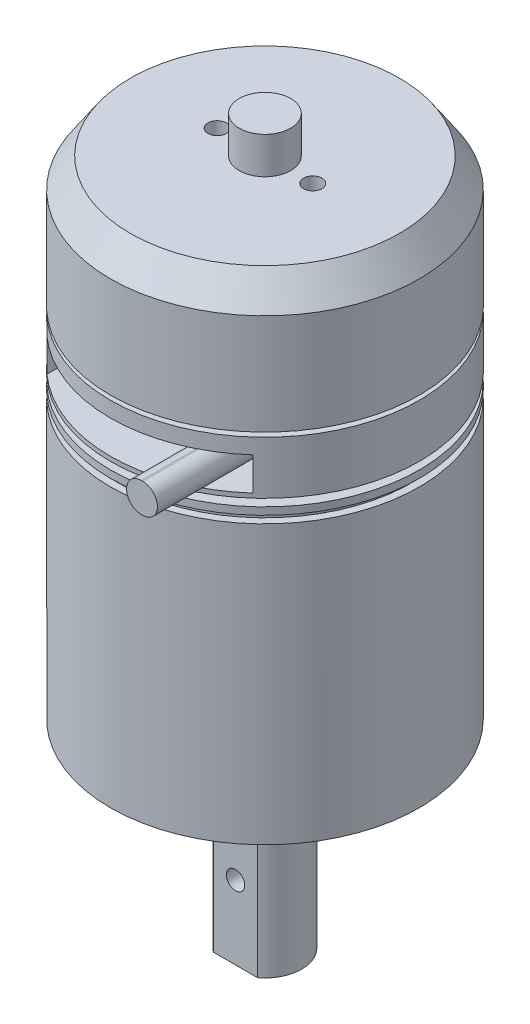
SolidWorks part; units mm, degrees
ref_plane "前视基准面" through (0, 0, 0) normal (0, 0, 1) x (1, 0, 0)
ref_plane "上视基准面" through (0, 0, 0) normal (0, 1, 0) x (1, 0, 0)
ref_plane "右视基准面" through (0, 0, 0) normal (1, 0, 0) x (0, 0, -1)
sketch "草图1" plane through (0, 0, 0) normal (0, 0, 1) x (1, 0, 0)
  line L0 (0, 0) -> (4.1, 0)
  line L1 (4.1, 0) -> (4.1, 6.7)
  line L2 (4.1, 6.7) -> (13.4, 6.7)
  line L3 (13.4, 6.7) -> (13.4, 8.7)
  line L4 (13.4, 8.7) -> (21, 8.7)
  line L5 (21, 8.7) -> (21, 10.2)
  line L6 (21, 10.2) -> (20, 10.2)
  line L7 (20, 10.2) -> (20, 11.2)
  line L8 (20, 11.2) -> (21, 11.2)
  line L9 (21, 11.2) -> (21, 12.2)
  line L10 (21, 12.2) -> (10, 12.2)
  line L11 (10, 12.2) -> (10, 13.2)
  line L12 (10, 13.2) -> (21, 13.2)
  line L13 (21, 13.2) -> (21, 20.4)
  line L14 (21, 20.4) -> (5, 20.4)
  line L15 (5, 20.4) -> (5, 21)
  line L16 (5, 21) -> (21, 21)
  line L17 (21, 21) -> (21, 34.7)
  line L18 (21, 34.7) -> (18.3, 38.7)
  line L19 (18.3, 38.7) -> (3.5, 38.7)
  line L20 (3.5, 38.7) -> (3.5, 43.7)
  line L21 (3.5, 43.7) -> (0, 43.7)
  line L22 (0, 43.7) -> (0, 0) construction
  line L23 (0, 0) -> (0, 43.7)
  dimension "D1" = 8.2
  dimension "D2" = 26.8
  dimension "D3" = 42
  dimension "D4" = 10
  dimension "D5" = 1.5
  dimension "D6" = 1
  dimension "D7" = 1
  dimension "D8" = 20
  dimension "D9" = 1
  dimension "D10" = 7.2
  dimension "D11" = 0.6
  dimension "D12" = 13.7
  dimension "D13" = 5
  dimension "D14" = 2
  dimension "D15" = 6.7
  dimension "D16" = 1
  dimension "D17" = 7
  dimension "D18" = 36.6
  dimension "D19" = 4
  dimension "D20" = 30
revolve "旋转1" add sketch "草图1" angle 360 about L22
ref_plane "基准面1" through (0, 0, 21) normal (0, 0, 1) x (1, 0, 0)
sketch "草图2" plane through (0, 0, 21) normal (0, 0, 1) x (1, 0, 0)
  line L1 (-14, 18.3) -> (14, 18.3)
  line L2 (-14, 18.3) -> (-14, 13.8)
  line L3 (-14, 13.8) -> (14, 13.8)
  line L4 (14, 18.3) -> (14, 13.8)
  line L5 (-14, 18.3) -> (14, 13.8) construction
  line L6 (-14, 13.8) -> (14, 18.3) construction
  line L7 (-21, 13.2) -> (21, 13.2) construction
  point P0 (0, 16.05)
  dimension "D1" = 28
  dimension "D2" = 4.5
  dimension "D3" = 0.6
extrude "切除-拉伸1" cut sketch "草图2" against normal blind 10
sketch "草图3" plane through (0, 0, 11) normal (0, 0, 1) x (1, 0, 0)
  line L0 (9.1851, 16.0532) -> (9.3851, 16.0532) construction
  line L1 (9.1851, 18.0532) -> (9.3851, 18.0532)
  line L2 (9.1851, 14.0532) -> (9.3851, 14.0532)
  arc A0 (9.1851, 18.0532) -> (9.1851, 14.0532) centre (9.1851, 16.0532) ccw
  arc A1 (9.3851, 14.0532) -> (9.3851, 18.0532) centre (9.3851, 16.0532) ccw
  point P2 (9.2851, 16.0532)
  dimension "D1" = 4
  dimension "D2" = 0.2
extrude "凸台-拉伸1" add sketch "草图3" along normal blind 15
hole_wizard "M3 螺纹孔1" positions "草图5" profile "草图6" tap size "M3" standard "GB"
sketch "草图5" plane through (0, 38.7, 0) normal (0, 1, 0) x (1, 0, 0)
  line L0 (0, 0) -> (0, 8.0606) construction
  point P0 (-6.5, 0)
  point P2 (6.5, 0)
  dimension "D1" = 13
sketch "草图6" plane through (-6.5, 38.7, 0) normal (1, 0, 0) x (0, 0, 1)
  line L0 (0, 0) -> (0, 4.7511)
  line L1 (0, 4.7511) -> (1.25, 4)
  line L2 (1.25, 4) -> (1.25, 0)
  line L5 (1.25, 0) -> (0, 0)
  line L10 (0, 4.7511) -> (-1.25, 4) construction
  line L11 (0, -6.35) -> (0, 107.95) construction
  dimension "螺纹孔钻头直径" = 2.5
  dimension "螺纹孔钻头深度" = 4
  dimension "导头角度" = 118
cosmetic thread "孔螺蚊线1" parameters "D1"=4, "D2"=3
cosmetic thread "孔螺蚊线2" parameters "D1"=4, "D2"=3
sketch "草图7" plane through (0, 0, 0) normal (0, 0, 1) x (1, 0, 0)
  line L0 (0, 8.7) -> (0, -54.6) construction
  line L1 (-13.4, 8.7) -> (13.4, 8.7) construction
  line L2 (0, -54.6) -> (5, -54.6)
  line L3 (5, -54.6) -> (5, -30.5)
  line L4 (5, -30.5) -> (8.275, -30.5)
  line L5 (13, -29.6) -> (13, -27.6)
  line L6 (13, -27.6) -> (21, -27.6)
  line L7 (21, -27.6) -> (21, 8.7)
  line L8 (-21, 8.7) -> (21, 8.7) construction
  line L9 (21, 8.7) -> (0, 8.7)
  line L10 (18.3, 38.7) -> (-18.3, 38.7) construction
  line L11 (13, -29.6) -> (8.275, -29.6)
  line L12 (8.275, -29.6) -> (8.275, -30.5)
  line L13 (0, 8.7) -> (0, -54.6)
  dimension "D1" = 66.3
  dimension "D2" = 2
  dimension "D3" = 0.9
  dimension "D4" = 27
  dimension "D5" = 26
  dimension "D6" = 10
  dimension "D7" = 16.55
revolve "旋转2" add sketch "草图7" angle 360 about L0
sketch "草图8" plane through (0, -54.6, 0) normal (0, -1, 0) x (1, 0, 0)
  line L0 (-3, 4) -> (3, 4)
  circle A0 centre (0, 0) radius 5 construction
  circle A1 centre (0, 0) radius 5 construction
  arc A2 (3, 4) -> (-3, 4) centre (0, 0) ccw
  dimension "D1" = 4
extrude "切除-拉伸2" cut sketch "草图8" against normal blind 20
hole_wizard "M4 螺纹孔1" positions "草图10" profile "草图9" tap size "M4" standard "GB"
sketch "草图10" plane through (0, -27.6, 0) normal (0, -1, 0) x (-1, 0, 0)
  circle A0 centre (0, 0) radius 17.5
  point P5 (0, -17.5)
  point P7 (-17.5, 0)
  point P9 (0, 17.5)
  point P11 (17.5, 0)
  dimension "D1" = 35
sketch "草图9" plane through (0, -27.6, 17.5) normal (1, 0, 0) x (0, 0, -1)
  line L0 (0, 0) -> (0, 11.0914)
  line L1 (0, 11.0914) -> (1.65, 10.1)
  line L2 (1.65, 10.1) -> (1.65, 0)
  line L5 (1.65, 0) -> (0, 0)
  line L10 (0, 11.0914) -> (-1.65, 10.1) construction
  line L11 (0, -6.35) -> (0, 107.95) construction
  dimension "螺纹孔钻头直径" = 3.3
  dimension "螺纹孔钻头深度" = 10.1
  dimension "导头角度" = 118
cosmetic thread "孔螺蚊线3" parameters "D1"=8, "D2"=4
cosmetic thread "孔螺蚊线4" parameters "D1"=8, "D2"=4
cosmetic thread "孔螺蚊线5" parameters "D1"=8, "D2"=4
cosmetic thread "孔螺蚊线6" parameters "D1"=8, "D2"=4
sketch "草图11" plane through (0, 0, 4) normal (0, 0, 1) x (1, 0, 0)
  line L0 (0, -54.6) -> (0, -36.079) construction
  line L1 (-3, -54.6) -> (3, -54.6) construction
  line L2 (-13.929, -44.6) -> (10.5915, -44.6) construction
  circle A0 centre (0, -44.6) radius 1.9071
  dimension "D1" = 10
hole_wizard "M3 螺纹孔2" positions "3D草图1" profile "草图12" tap size "M3" standard "GB" end condition through all
sketch3d "3D草图1"
  point P0 (0, -44.6, 4)
sketch "草图12" plane through (0, -44.6, 4) normal (1, 0, 0) x (0, -1, 0)
  line L0 (0, 0) -> (0, 25)
  line L1 (0, 25) -> (1.25, 25)
  line L2 (1.25, 25) -> (1.25, 0)
  line L3 (10, 0) -> (10, 9) construction
  line L5 (1.25, 0) -> (0, 0)
  line L11 (0, -6.35) -> (0, 107.95) construction
  dimension "螺纹线主直径" = 2.5
  dimension "通孔螺纹孔钻头深度" = 25
sketch "草图15" plane through (0, -54.6, 0) normal (0, -1, 0) x (1, 0, 0)
  point P0 (0, 0)
hole_wizard "M5 螺纹孔1" positions "3D草图5" profile "草图16" tap size "M5" standard "GB"
sketch3d "3D草图5"
  point P0 (0, -54.6, 0)
  point P3 (0, -54.6, 0)
sketch "草图16" plane through (0, -54.6, 0) normal (1, 0, 0) x (0, 0, -1)
  line L0 (0, 0) -> (0, 15.2618)
  line L1 (0, 15.2618) -> (2.1, 14)
  line L2 (2.1, 14) -> (2.1, 0)
  line L5 (2.1, 0) -> (0, 0)
  line L10 (0, 15.2618) -> (-2.1, 14) construction
  line L11 (0, -6.35) -> (0, 107.95) construction
  dimension "螺纹孔钻头直径" = 4.2
  dimension "螺纹孔钻头深度" = 14
  dimension "导头角度" = 118
cosmetic thread "孔螺蚊线7" parameters "D1"=10, "D2"=5
cosmetic thread "孔螺蚊线8" parameters "D1"=10, "D2"=5
